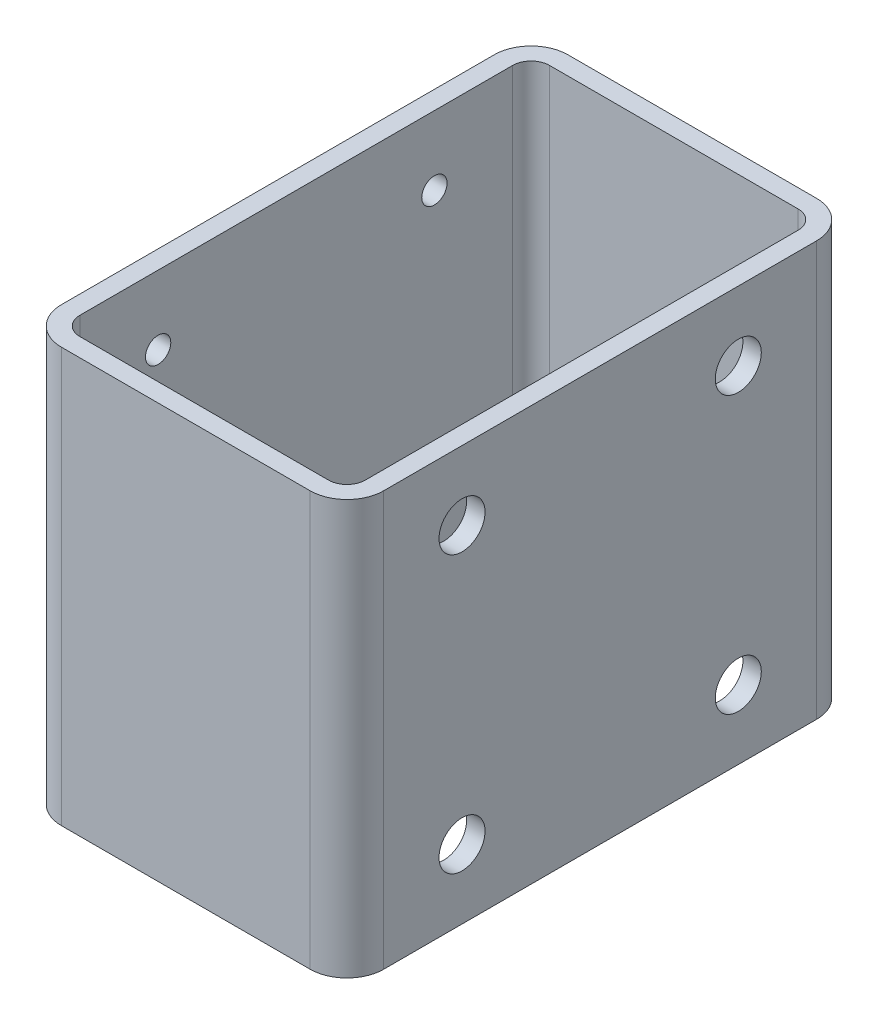
SolidWorks part; units mm, degrees
material "Q235-A"
ref_plane "前视基准面" through (0, 0, 0) normal (0, 0, 1) x (1, 0, 0)
ref_plane "上视基准面" through (0, 0, 0) normal (0, 1, 0) x (1, 0, 0)
ref_plane "右视基准面" through (0, 0, 0) normal (1, 0, 0) x (0, 0, -1)
sketch "草图1" plane through (0, 0, 0) normal (0, 0, 1) x (1, 0, 0)
  line L0 (0, 0) -> (0, 180)
  dimension "D1" = 180
other "Tube (rectangular) 220 X 140 X 8.0(1)"
ref_plane "基准面1" through (0, 0, 0) normal (0, 1, 0) x (-1, 0, 0)
sketch "Sketch1" plane through (0, 0, 0) normal (0, 1, 0) x (-1, 0, 0)
  line L0 (-54, -102) -> (54, -102)
  line L1 (-62, -94) -> (-62, 94)
  line L2 (54, 102) -> (-54, 102)
  line L3 (62, 94) -> (62, -94)
  line L4 (-54, -110) -> (54, -110)
  line L5 (-70, -94) -> (-70, 94)
  line L6 (54, 110) -> (-54, 110)
  line L7 (70, 94) -> (70, -94)
  line L8 (-70, 0) -> (-62, 0) construction
  line L9 (-62, 0) -> (62, 0) construction
  line L10 (62, 0) -> (70, 0) construction
  line L11 (0, 110) -> (0, 102) construction
  line L12 (0, 102) -> (0, -102) construction
  line L13 (0, -102) -> (0, -110) construction
  arc A0 (70, 94) -> (54, 110) centre (54, 94) ccw
  arc A1 (54, -110) -> (70, -94) centre (54, -94) ccw
  arc A2 (-70, -94) -> (-54, -110) centre (-54, -94) ccw
  arc A3 (-54, 110) -> (-70, 94) centre (-54, 94) ccw
  arc A4 (-54, 102) -> (-62, 94) centre (-54, 94) ccw
  arc A5 (62, 94) -> (54, 102) centre (54, 94) ccw
  arc A6 (54, -102) -> (62, -94) centre (54, -94) ccw
  arc A7 (-62, -94) -> (-54, -102) centre (-54, -94) ccw
  point P6 (-70, 110)
  point P33 (-70, -110)
  point P34 (70, -110)
  point P36 (70, 110)
  point P37 (0, 0)
  dimension "D1" = 16
  dimension "Thickness" = 8
  dimension "V_leg" = 220
  dimension "H_leg" = 140
sketch "草图5" plane through (-70, 0, 0) normal (-1, 0, 0) x (0, 0, 1)
  line L0 (0, 0) -> (0, 219.2188) construction
  line L1 (-94, 180) -> (94, 180) construction
  circle A0 centre (-60, 30) radius 5.5
  circle A1 centre (60, 30) radius 5.5
  circle A2 centre (-60, 150) radius 5.5
  circle A3 centre (60, 150) radius 5.5
  dimension "D1" = 120
  dimension "D3" = 11
  dimension "D2" = 60
  dimension "D4" = 120
  dimension "D5" = 30
extrude "切除-拉伸1" cut sketch "草图5" against normal blind 10
sketch "草图6" plane through (70, 0, 0) normal (1, 0, 0) x (0, 0, -1)
  circle A0 centre (-60, 150) radius 10
  circle A1 centre (60, 150) radius 10
  circle A2 centre (-60, 30) radius 10
  circle A3 centre (60, 30) radius 10
  dimension "D1" = 20
extrude "切除-拉伸2" cut sketch "草图6" against normal blind 10
